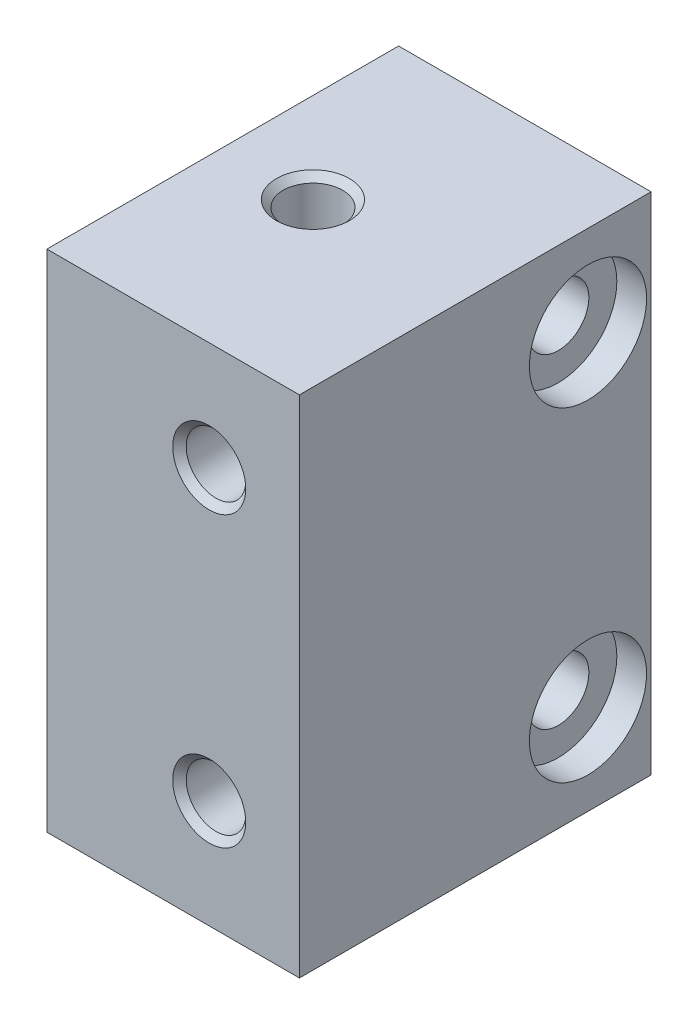
SolidWorks part; units mm, degrees
ref_plane "Plan de face" through (0, 0, 0) normal (0, 0, 1) x (1, 0, 0)
ref_plane "Plan de dessus" through (0, 0, 0) normal (0, 1, 0) x (1, 0, 0)
ref_plane "Plan de droite" through (0, 0, 0) normal (1, 0, 0) x (0, 0, -1)
sketch "Esquisse1" plane through (0, 0, 0) normal (0, 0, 1) x (1, 0, 0)
  line L0 (21.905, -14.0022) -> (7.905, -14.0022)
  line L1 (21.905, -14.0022) -> (21.905, 13.9978)
  line L2 (7.905, -14.0022) -> (7.905, 13.9978)
  line L3 (21.905, 13.9978) -> (7.905, 13.9978)
  dimension "D1" = 28
  dimension "D2" = 14
extrude "Boss.-Extru.1" add sketch "Esquisse1" along normal blind 19.5
sketch "Esquisse2" plane through (21.905, 0, 0) normal (1, 0, 0) x (0, 0, -1)
  line L0 (-19.5, -0.0022) -> (-3.5, -0.0022) construction
  line L1 (-19.5, -14.0022) -> (-19.5, 13.9978) construction
  line L2 (-3.5, -9.0022) -> (-3.5, 8.9978) construction
  point P7 (-3.5, -0.0022)
  dimension "D1" = 16
  dimension "D2" = 18
hole_wizard "Chambrage pour Vis à tête ronde à 6 pans creux M31" positions "Esquisse3" profile "Esquisse4" counterbore size "M3" standard "Ansi Metric" end condition up to next
sketch "Esquisse3" plane through (21.905, 0, 0) normal (1, 0, 0) x (0, 0, -1)
  point P0 (-3.5, 8.9978)
  point P3 (-3.5, -9.0022)
sketch "Esquisse4" plane through (21.905, 8.9978, 3.5) normal (0, 1, 0) x (0, 0, -1)
  line L0 (0, 0) -> (0, 14)
  line L1 (0, 14) -> (1.7, 14)
  line L3 (1.7, 14) -> (1.7, 1.65)
  line L4 (1.7, 1.65) -> (3.25, 1.65)
  line L5 (3.25, 1.65) -> (3.25, 0)
  line L7 (3.25, 0) -> (0, 0)
  line L11 (0, -6.35) -> (0, 107.95) construction
  dimension "Diamètre du perçage jusqu'au prochain" = 3.4
  dimension "Profondeur du perçage jusqu'au prochain" = 14
  dimension "Diamètre du chambrage" = 6.5
  dimension "Profondeur du chambrage" = 1.65
sketch "Esquisse5" plane through (21.905, 0, 0) normal (1, 0, 0) x (0, 0, -1)
  line L0 (-13, 13.9978) -> (-13, -14.0022) construction
  line L1 (-19.5, 13.9978) -> (0, 13.9978) construction
  line L2 (-19.5, -14.0022) -> (0, -14.0022) construction
  line L3 (-13, -0.0022) -> (0, -0.0022) construction
  line L4 (0, -14.0022) -> (0, 13.9978) construction
  point P6 (-13, 7.9978)
  point P7 (-13, -8.0022)
  dimension "D1" = 8
  dimension "D2" = 8
  dimension "D3" = 13
sketch "Esquisse9" plane through (0, 0, 19.5) normal (0, 0, 1) x (1, 0, 0)
  line L0 (16.905, 13.9978) -> (16.905, -14.0022) construction
  line L1 (21.905, 13.9978) -> (7.905, 13.9978) construction
  line L2 (7.905, -14.0022) -> (21.905, -14.0022) construction
  line L3 (21.905, -14.0022) -> (21.905, 13.9978) construction
  point P6 (16.905, 7.9978)
  point P7 (16.905, -8.0022)
  dimension "D1" = 6
  dimension "D2" = 6
  dimension "D3" = 5
  dimension "D4" = 16
hole_wizard "Trou taraudé M4x0.72" positions "Esquisse10" profile "Esquisse12" tap size "M4x0.7" standard "Ansi Metric"
sketch "Esquisse10" plane through (0, 0, 19.5) normal (0, 0, 1) x (1, 0, 0)
  point P0 (16.905, 7.9978)
  point P3 (16.905, -8.0022)
sketch "Esquisse12" plane through (16.905, 7.9978, 19.5) normal (1, 0, 0) x (0, -1, 0)
  line L0 (0, 0) -> (0, 12.4914)
  line L1 (0, 12.4914) -> (1.65, 11.5)
  line L2 (1.65, 11.5) -> (1.65, 0.375)
  line L3 (1.65, 0.375) -> (2.025, 0)
  line L5 (2.025, 0) -> (0, 0)
  line L6 (-1.65, 0.375) -> (-2.025, 0) construction
  line L10 (0, 12.4914) -> (-1.65, 11.5) construction
  line L11 (0, -6.35) -> (0, 107.95) construction
  dimension "Diamètre du trou pour taraudage" = 3.3
  dimension "Profondeur du trou pour taraudage" = 11.5
  dimension "Diamètre du fraisage entrant" = 4.05
  dimension "Angle du fraisage entrant" = 90
  dimension "Angle de pointe" = 118
cosmetic thread "Filetage de perçage3" parameters "D1"=8, "D2"=4
cosmetic thread "Filetage de perçage4" parameters "D1"=8, "D2"=4
sketch "Esquisse14" plane through (0, 13.9978, 0) normal (0, 1, 0) x (1, 0, 0)
  line L0 (12.905, -19.5) -> (12.905, 0)
  line L1 (21.905, -19.5) -> (7.905, -19.5) construction
  line L2 (21.905, 0) -> (7.905, 0) construction
  line L3 (7.905, -19.5) -> (7.905, 0) construction
  point P6 (12.905, -9.75)
  dimension "D1" = 5
hole_wizard "Trou taraudé M4x0.73" positions "Esquisse3D1" profile "Esquisse15" tap size "M4x0.7" standard "Ansi Metric" end condition through all
sketch3d "Esquisse3D1"
  point P0 (12.905, 13.9978, 9.75)
  point P8 (12.905, 13.9978, 9.75)
cosmetic thread "Filetage de perçage6" parameters "D2"=4
sketch "Esquisse15" plane through (12.905, 13.9978, 9.75) normal (1, 0, 0) x (0, 0, 1)
  line L0 (0, 0) -> (0, 28)
  line L1 (0, 28) -> (2.025, 28)
  line L2 (1.65, 27.625) -> (1.65, 0.375)
  line L3 (1.65, 0.375) -> (2.025, 0)
  line L5 (2.025, 0) -> (0, 0)
  line L6 (-1.65, 0.375) -> (-2.025, 0) construction
  line L7 (2.025, 28) -> (1.65, 27.625)
  line L8 (-2.025, 28) -> (-1.65, 27.625) construction
  line L11 (0, -6.35) -> (0, 107.95) construction
  dimension "Diamètre du trou pour taraudage jusqu'au prochain" = 3.3
  dimension "Profondeur du trou pour taraudage jusqu'au prochain" = 28
  dimension "Diamètre du fraisage entrant" = 4.05
  dimension "Angle du fraisage entrant" = 90
  dimension "Diamètre du fraisage débouchant" = 4.05
  dimension "Angle du fraisage débouchant" = 90
